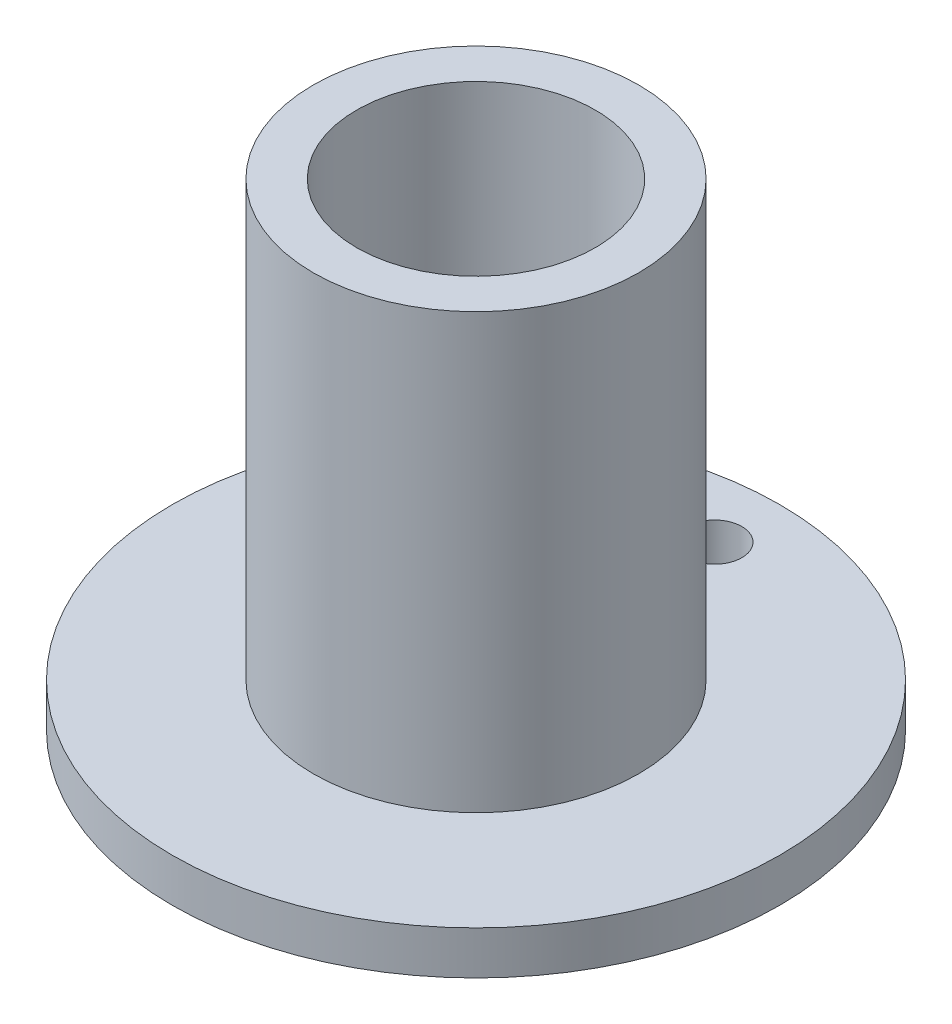
SolidWorks part; units mm, degrees
ref_plane "Front Plane" through (0, 0, 0) normal (0, 0, 1) x (1, 0, 0)
ref_plane "Top Plane" through (0, 0, 0) normal (0, 1, 0) x (1, 0, 0)
ref_plane "Right Plane" through (0, 0, 0) normal (1, 0, 0) x (0, 0, -1)
sketch "Sketch1" plane through (0, 0, 0) normal (0, 1, 0) x (1, 0, 0)
  circle A0 centre (0, 0) radius 14
  circle A1 centre (0, 0) radius 5.5
  dimension "D1" = 11
  dimension "D2" = 28
extrude "Boss-Extrude1" add sketch "Sketch1" along normal blind 2
sketch "Sketch2" plane through (0, 2, 0) normal (0, 1, 0) x (1, 0, 0)
  circle A0 centre (0, 11) radius 1.25
  dimension "D2" = 2.5
  dimension "D1" = 11
extrude "Cut-Extrude1" cut sketch "Sketch2" against normal up to surface (2 mm away) up to face at (0, 0, 14)
sketch "Sketch3" plane through (0, 2, 0) normal (0, 1, 0) x (1, 0, 0)
  circle A0 centre (0, 0) radius 5.5
  circle A1 centre (0, 0) radius 7.5
  dimension "D1" = 15
extrude "Boss-Extrude2" add sketch "Sketch3" along normal blind 20
